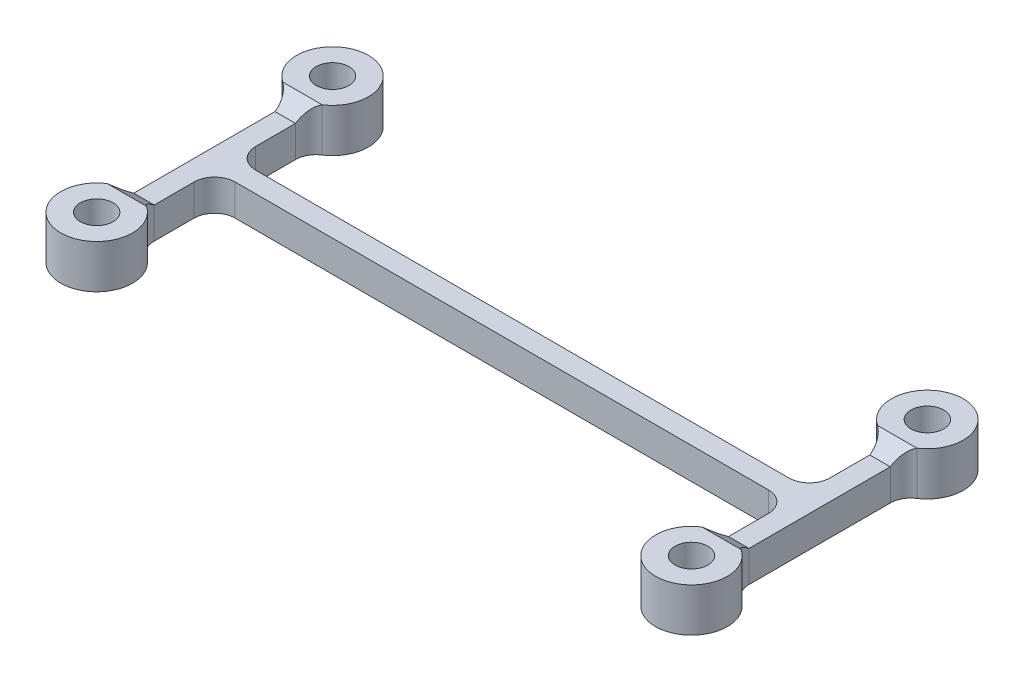
SolidWorks part; units mm, degrees
ref_plane "Front Plane" through (0, 0, 0) normal (0, 0, 1) x (1, 0, 0)
ref_plane "Top Plane" through (0, 0, 0) normal (0, 1, 0) x (1, 0, 0)
ref_plane "Right Plane" through (0, 0, 0) normal (1, 0, 0) x (0, 0, -1)
sketch "Sketch1" plane through (0, 0, 0) normal (0, 1, 0) x (1, 0, 0)
  line L0 (-32.5, -16.3186) -> (32.5, -16.3186)
  line L1 (-29, 10.1814) -> (29, 10.1814)
  line L2 (-29, 10.1814) -> (-29, -12.8186)
  line L3 (-32.5, 13.6814) -> (32.5, 13.6814)
  line L4 (-32.5, 13.6814) -> (-32.5, -16.3186)
  line L5 (-29, -12.8186) -> (29, -12.8186)
  line L6 (32.5, 13.6814) -> (32.5, -16.3186)
  line L7 (29, 10.1814) -> (29, -12.8186)
  line L8 (8.9, 16.7818) -> (8.9, 15.499)
  line L9 (21.5, 16.7818) -> (21.5, 15.499)
  dimension "D1" = 65
  dimension "D2" = 30
  dimension "D3" = 58
  dimension "D4" = 23
  dimension "D5" = 3.5
  dimension "D6" = 3.5
sketch "Sketch2" plane through (0, 0, 0) normal (0, 1, 0) x (1, 0, 0)
  line L0 (-29, 6.6814) -> (-29, -9.3186) construction
  line L1 (29, 6.6814) -> (29, -9.3186) construction
  line L2 (-29, -1.3186) -> (29, -1.3186) construction
  line L3 (-26, -2.3186) -> (26, -2.3186)
  line L4 (-30, 5.5716) -> (-30, -8.2088)
  line L5 (28, 5.5716) -> (28, 1.6814)
  line L6 (-26, -0.3186) -> (26, -0.3186)
  line L7 (-28, 5.5716) -> (-28, 1.6814)
  line L8 (30, 5.5716) -> (30, -8.2088)
  line L9 (-30, 6.6814) -> (-30, -9.3186) construction
  line L10 (-28, 6.6814) -> (-28, -9.3186) construction
  line L11 (30, 6.6814) -> (30, -9.3186) construction
  line L12 (28, 6.6814) -> (28, -9.3186) construction
  line L13 (-29, -0.3186) -> (29, -0.3186) construction
  line L14 (-29, -2.3186) -> (29, -2.3186) construction
  line L15 (-28, -4.3186) -> (-28, -8.2088)
  line L16 (28, -4.3186) -> (28, -8.2088)
  arc A0 (-27.0909, 7.2479) -> (-30.9091, 7.2479) centre (-29, 10.1814) ccw
  arc A1 (-30.9091, -9.8851) -> (-27.0909, -9.8851) centre (-29, -12.8186) ccw
  arc A2 (30.9091, 7.2479) -> (27.0909, 7.2479) centre (29, 10.1814) ccw
  arc A3 (27.0909, -9.8851) -> (30.9091, -9.8851) centre (29, -12.8186) ccw
  arc A4 (30.9091, -9.8851) -> (30, -8.2088) centre (32, -8.2088) cw
  arc A5 (28, -8.2088) -> (27.0909, -9.8851) centre (26, -8.2088) cw
  arc A6 (28, -4.3186) -> (26, -2.3186) centre (26, -4.3186) ccw
  arc A7 (28, 5.5716) -> (27.0909, 7.2479) centre (26, 5.5716) ccw
  arc A8 (26, -0.3186) -> (28, 1.6814) centre (26, 1.6814) ccw
  arc A9 (30, 5.5716) -> (30.9091, 7.2479) centre (32, 5.5716) cw
  arc A10 (-26, -0.3186) -> (-28, 1.6814) centre (-26, 1.6814) cw
  arc A11 (-26, -2.3186) -> (-28, -4.3186) centre (-26, -4.3186) ccw
  arc A12 (-27.0909, -9.8851) -> (-28, -8.2088) centre (-26, -8.2088) cw
  arc A13 (-30.9091, -9.8851) -> (-30, -8.2088) centre (-32, -8.2088) ccw
  arc A14 (-27.0909, 7.2479) -> (-28, 5.5716) centre (-26, 5.5716) ccw
  arc A15 (-30, 5.5716) -> (-30.9091, 7.2479) centre (-32, 5.5716) ccw
  point P51 (-28, -2.3186)
  dimension "D1" = 1
  dimension "D3" = 2
  dimension "D2" = 1
extrude "Boss-Extrude1" add sketch "Sketch2" along normal blind 4.25
hole_wizard "Ø3.2 (3.2) Diameter Hole1" positions "Sketch4" profile "Sketch3" hole size "Ø3.2" standard "ANSI Metric" end condition through all
sketch "Sketch4" plane through (0, 4.25, 0) normal (0, 1, 0) x (1, 0, 0)
  point P0 (-29, -12.8186)
  point P4 (-29, 10.1814)
  point P8 (29, 10.1814)
  point P12 (29, -12.8186)
sketch "Sketch3" plane through (-29, 4.25, 12.8186) normal (1, 0, 0) x (0, 0, 1)
  line L0 (0, 0) -> (0, 4.25)
  line L1 (0, 4.25) -> (1.6, 4.25)
  line L2 (1.6, 4.25) -> (1.6, 0)
  line L5 (1.6, 0) -> (0, 0)
  line L11 (0, -6.35) -> (0, 107.95) construction
  dimension "Thru Hole Dia." = 3.2
  dimension "Thru Hole Depth" = 4.25
sketch "Sketch5" plane through (0, 0, 0) normal (1, 0, 0) x (0, 0, -1)
  line L0 (-8.2088, 3.0555) -> (5.5716, 3.0555)
  line L1 (-8.2088, 4.25) -> (-8.2088, 0) construction
  line L2 (5.5716, 4.25) -> (5.5716, 0) construction
  line L3 (5.5716, 3.0555) -> (7.2479, 4.25)
  line L4 (7.2479, 4.25) -> (-9.8851, 4.25)
  line L5 (-9.8851, 4.25) -> (-8.2088, 3.0555)
extrude "Cut-Extrude1" cut sketch "Sketch5" against normal through all both and the other way through all
